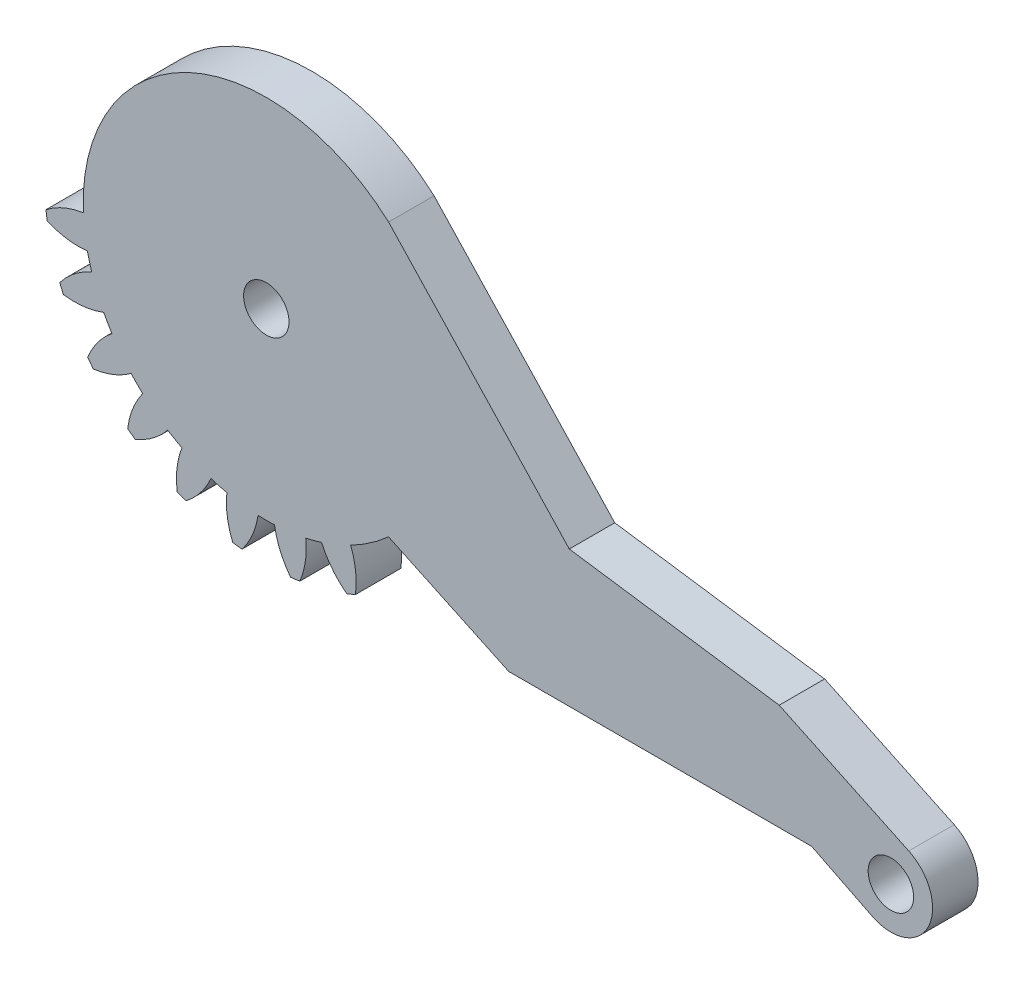
SolidWorks part; units mm, degrees
ref_plane "Front Plane" through (0, 0, 0) normal (0, 0, 1) x (1, 0, 0)
ref_plane "Top Plane" through (0, 0, 0) normal (0, 1, 0) x (1, 0, 0)
ref_plane "Right Plane" through (0, 0, 0) normal (1, 0, 0) x (0, 0, -1)
sketch "Sketch2" plane through (0, 0, 0) normal (0, 0, 1) x (1, 0, 0)
  line L0 (0, 0.8189) -> (0, 15.4489) construction
  line L1 (20, -2.9114) -> (33.8564, -4.9114)
  line L2 (8.0727, 9.8189) -> (20, -2.9114)
  line L3 (16, -11.9114) -> (8.0727, -8.1811)
  line L4 (33.8564, -4.9114) -> (42.4082, -8.9667)
  line L5 (16, -11.9114) -> (36, -11.9114)
  line L6 (36, -11.9114) -> (40, -13.9114)
  circle A0 centre (0, 0.8189) radius 14.63
  circle A1 centre (0, 0.8189) radius 12.09
  arc A3 (1.6018, 15.3609) -> (0.5411, 12.8968) centre (5.876, 12.0607) ccw
  arc A4 (-1.6018, 15.3609) -> (-0.5411, 12.8968) centre (-5.876, 12.0607) cw
  arc A5 (5.311, 14.4508) -> (3.6487, 12.3452) centre (8.5854, 10.1568) ccw
  arc A6 (2.2165, 15.28) -> (2.6033, 12.6253) centre (-2.7662, 13.1985) cw
  arc A7 (8.6582, 12.6117) -> (6.5076, 11.0081) centre (10.7097, 7.6166) ccw
  arc A8 (5.8838, 14.2136) -> (5.5703, 11.5492) centre (0.5322, 13.4926) cw
  arc A9 (11.4154, 9.969) -> (8.923, 8.9766) centre (12.1041, 4.6131) ccw
  arc A10 (9.1501, 12.2343) -> (8.1577, 9.7418) centre (3.7942, 12.923) cw
  arc A11 (13.3947, 6.7027) -> (10.7303, 6.3892) centre (12.6737, 1.351) ccw
  arc A12 (11.7929, 9.4771) -> (10.1892, 7.3264) centre (6.7977, 11.5285) cw
  arc A13 (14.4611, 3.0354) -> (11.8064, 3.4222) centre (12.3796, -1.9473) ccw
  arc A14 (13.632, 6.1299) -> (11.5263, 4.4675) centre (9.338, 9.4042) cw
  arc A15 (14.542, -0.7829) -> (12.0779, 0.2778) centre (11.2418, -5.0571) ccw
  arc A16 (14.542, 2.4207) -> (12.0779, 1.36) centre (11.2418, 6.6949) cw
  arc A17 (13.632, -4.4921) -> (11.5263, -2.8298) centre (9.338, -7.7665) ccw
  arc A18 (14.4611, -1.3976) -> (11.8064, -1.7844) centre (12.3796, 3.585) cw
  arc A19 (11.7929, -7.8394) -> (10.1892, -5.6887) centre (6.7977, -9.8908) ccw
  arc A20 (13.3947, -5.0649) -> (10.7303, -4.7515) centre (12.6737, 0.2867) cw
  arc A21 (9.1501, -10.5966) -> (8.1577, -8.1041) centre (3.7942, -11.2853) ccw
  arc A22 (11.4154, -8.3312) -> (8.923, -7.3389) centre (12.1041, -2.9753) cw
  arc A23 (5.8838, -12.5758) -> (5.5703, -9.9114) centre (0.5322, -11.8548) ccw
  arc A24 (8.6582, -10.974) -> (6.5076, -9.3703) centre (10.7097, -5.9788) cw
  arc A25 (2.2165, -13.6422) -> (2.6033, -10.9875) centre (-2.7662, -11.5607) ccw
  arc A26 (5.311, -12.8131) -> (3.6487, -10.7074) centre (8.5854, -8.5191) cw
  arc A27 (-1.6018, -13.7232) -> (-0.5411, -11.259) centre (-5.876, -10.423) ccw
  arc A28 (1.6018, -13.7232) -> (0.5411, -11.259) centre (5.876, -10.423) cw
  arc A29 (-5.311, -12.8131) -> (-3.6487, -10.7074) centre (-8.5854, -8.5191) ccw
  arc A30 (-2.2165, -13.6422) -> (-2.6033, -10.9875) centre (2.7662, -11.5607) cw
  arc A31 (-8.6582, -10.974) -> (-6.5076, -9.3703) centre (-10.7097, -5.9788) ccw
  arc A32 (-5.8838, -12.5758) -> (-5.5703, -9.9114) centre (-0.5322, -11.8548) cw
  arc A33 (-11.4154, -8.3312) -> (-8.923, -7.3389) centre (-12.1041, -2.9753) ccw
  arc A34 (-9.1501, -10.5966) -> (-8.1577, -8.1041) centre (-3.7942, -11.2853) cw
  arc A35 (-13.3947, -5.0649) -> (-10.7303, -4.7515) centre (-12.6737, 0.2867) ccw
  arc A36 (-11.7929, -7.8394) -> (-10.1892, -5.6887) centre (-6.7977, -9.8908) cw
  arc A37 (-14.4611, -1.3976) -> (-11.8064, -1.7844) centre (-12.3796, 3.585) ccw
  arc A38 (-13.632, -4.4921) -> (-11.5263, -2.8298) centre (-9.338, -7.7665) cw
  arc A39 (-14.542, 2.4207) -> (-12.0779, 1.36) centre (-11.2418, 6.6949) ccw
  arc A40 (-14.542, -0.7829) -> (-12.0779, 0.2778) centre (-11.2418, -5.0571) cw
  arc A41 (-13.632, 6.1299) -> (-11.5263, 4.4675) centre (-9.338, 9.4042) ccw
  arc A42 (-14.4611, 3.0354) -> (-11.8064, 3.4222) centre (-12.3796, -1.9473) cw
  arc A43 (-11.7929, 9.4771) -> (-10.1892, 7.3264) centre (-6.7977, 11.5285) ccw
  arc A44 (-13.3947, 6.7027) -> (-10.7303, 6.3892) centre (-12.6737, 1.351) cw
  arc A45 (-9.1501, 12.2343) -> (-8.1577, 9.7418) centre (-3.7942, 12.923) ccw
  arc A46 (-11.4154, 9.969) -> (-8.923, 8.9766) centre (-12.1041, 4.6131) cw
  arc A47 (-5.8838, 14.2136) -> (-5.5703, 11.5492) centre (-0.5322, 13.4926) ccw
  arc A48 (-8.6582, 12.6117) -> (-6.5076, 11.0081) centre (-10.7097, 7.6166) cw
  arc A49 (-2.2165, 15.28) -> (-2.6033, 12.6253) centre (2.7662, 13.1985) ccw
  arc A50 (-5.311, 14.4508) -> (-3.6487, 12.3452) centre (-8.5854, 10.1568) cw
  arc A51 (42.4082, -8.9667) -> (40, -13.9114) centre (41.2299, -11.4516) cw
  circle A52 centre (41.2299, -11.4516) radius 1.5
  circle A53 centre (0, 0.8189) radius 1.5
  point P154 (0, 0.8189)
  dimension "D2" = 24.18
  dimension "D3" = 29.26
  dimension "D4" = 0.62
  dimension "D6" = 2.08
  dimension "D8" = 16
  dimension "D9" = 18
  dimension "D10" = 3
  dimension "D20" = 3
  dimension "D5" = 5.4
  dimension "D11" = 4
  dimension "D12" = 2
  dimension "D13" = 20
  dimension "D14" = 4
  dimension "D15" = 5.5
  dimension "D16" = 7
  dimension "D17" = 14
  dimension "D18" = 2
  dimension "D19" = 9
  dimension "D7" = 24
extrude "Boss-Extrude2" add sketch "Sketch2" along normal blind 3
